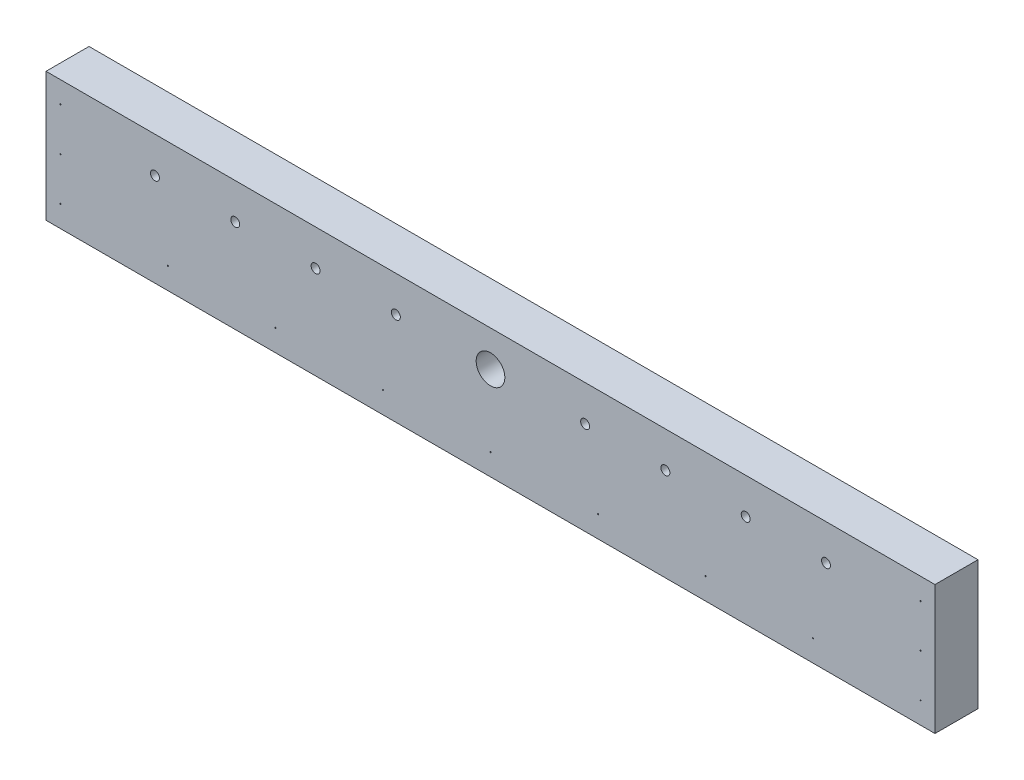
SolidWorks part; units mm, degrees
material "Maple"
ref_plane "Front Plane" through (0, 0, 0) normal (0, 0, 1) x (1, 0, 0)
ref_plane "Top Plane" through (0, 0, 0) normal (0, 1, 0) x (1, 0, 0)
ref_plane "Right Plane" through (0, 0, 0) normal (1, 0, 0) x (0, 0, -1)
sketch "Sketch1" plane through (0, 0, 0) normal (0, 0, 1) x (1, 0, 0)
  line L1 (0, 0) -> (1574.8, 0)
  line L2 (0, 0) -> (0, 228.6)
  line L3 (0, 228.6) -> (1574.8, 228.6)
  line L4 (1574.8, 0) -> (1574.8, 228.6)
  dimension "D1" = 1574.8
  dimension "D2" = 228.6
extrude "Boss-Extrude1" add sketch "Sketch1" along normal blind 76.2
sketch "Sketch2" plane through (0, 0, 76.2) normal (0, 0, 1) x (1, 0, 0)
  line L0 (0, 165.1) -> (1574.8, 165.1) construction
  line L1 (0, 228.6) -> (0, 0) construction
  line L2 (1574.8, 0) -> (1574.8, 228.6) construction
  line L3 (0, 0) -> (1574.8, 0) construction
  circle A0 centre (193.04, 165.1) radius 7.9375
  circle A1 centre (335.28, 165.1) radius 7.9375
  circle A2 centre (477.52, 165.1) radius 7.9375
  circle A3 centre (619.76, 165.1) radius 7.9375
  circle A5 centre (955.04, 165.1) radius 7.9375
  circle A6 centre (1097.28, 165.1) radius 7.9375
  circle A7 centre (1239.52, 165.1) radius 7.9375
  circle A8 centre (1381.76, 165.1) radius 7.9375
  dimension "D1" = 15.875
  dimension "D2" = 15.875
  dimension "D3" = 15.875
  dimension "D4" = 15.875
  dimension "D6" = 15.875
  dimension "D7" = 15.875
  dimension "D8" = 15.875
  dimension "D9" = 15.875
  dimension "D12" = 477.52
  dimension "D13" = 619.76
  dimension "D10" = 193.04
  dimension "D11" = 335.28
  dimension "D14" = 193.04
  dimension "D15" = 335.28
  dimension "D16" = 477.52
  dimension "D17" = 619.76
  dimension "D18" = 165.1
extrude "Cut-Extrude1" cut sketch "Sketch2" against normal through all
sketch "Sketch3" plane through (0, 0, 76.2) normal (0, 0, 1) x (1, 0, 0)
  line L0 (1574.8, 0) -> (1574.8, 228.6) construction
  line L1 (0, 0) -> (1574.8, 0) construction
  line L2 (1574.8, 228.6) -> (0, 228.6) construction
  line L3 (787.4, 0) -> (787.4, 228.6) construction
  circle A0 centre (1549.4, 38.1) radius 0.9922
  circle A1 centre (1549.4, 190.5) radius 1.016
  circle A2 centre (1549.4, 114.3) radius 1.016
  circle A3 centre (25.4, 38.1) radius 0.9922
  circle A4 centre (25.4, 114.3) radius 1.016
  circle A5 centre (25.4, 190.5) radius 1.016
  circle A6 centre (215.9, 38.1) radius 1.016
  circle A7 centre (406.4, 38.1) radius 1.016
  circle A8 centre (596.9, 38.1) radius 1.016
  circle A9 centre (787.4, 38.1) radius 1.016
  circle A10 centre (977.9, 38.1) radius 1.016
  circle A11 centre (1168.4, 38.1) radius 1.016
  circle A12 centre (1358.9, 38.1) radius 1.016
  point P12 (1574.8, 114.3)
  dimension "D1" = 1.9844
  dimension "D6" = 2.032
  dimension "D8" = 2.032
  dimension "D13" = 2.032
  dimension "D14" = 2.032
  dimension "D15" = 2.032
  dimension "D16" = 2.032
  dimension "D2" = 25.4
  dimension "D3" = 38.1
  dimension "D4" = 38.1
  dimension "D5" = 25.4
  dimension "D7" = 25.4
  dimension "D9" = 0
  dimension "D10" = 190.5
  dimension "D11" = 190.5
  dimension "D12" = 190.5
extrude "Cut-Extrude2" cut sketch "Sketch3" against normal blind 76.2
sketch "Sketch4" plane through (0, 0, 76.2) normal (0, 0, 1) x (1, 0, 0)
  line L0 (1574.8, 228.6) -> (0, 228.6) construction
  line L2 (1574.8, 0) -> (1574.8, 228.6) construction
  circle A0 centre (787.4, 165.1) radius 25.4
  dimension "D2" = 50.8
  dimension "D1" = 63.5
  dimension "D3" = 787.4
extrude "Cut-Extrude3" cut sketch "Sketch4" against normal through all
